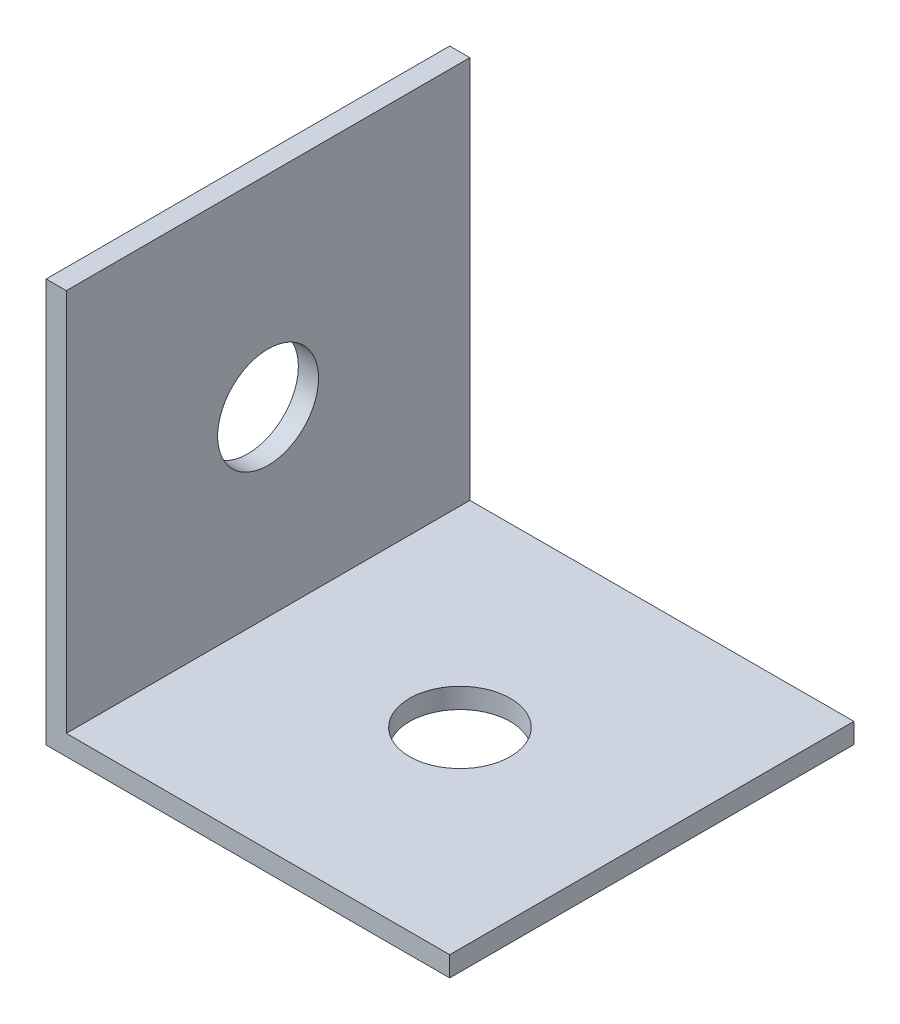
SolidWorks part; units mm, degrees
ref_plane "Front Plane" through (0, 0, 0) normal (0, 0, 1) x (1, 0, 0)
ref_plane "Top Plane" through (0, 0, 0) normal (0, 1, 0) x (1, 0, 0)
ref_plane "Right Plane" through (0, 0, 0) normal (1, 0, 0) x (0, 0, -1)
sketch "Sketch1" plane through (0, 0, 0) normal (1, 0, 0) x (0, 0, -1)
  line L1 (-12.7, 12.7) -> (12.7, 12.7)
  line L2 (-12.7, 12.7) -> (-12.7, -12.7)
  line L3 (-12.7, -12.7) -> (12.7, -12.7)
  line L4 (12.7, 12.7) -> (12.7, -12.7)
  line L5 (-12.7, 12.7) -> (12.7, -12.7) construction
  line L6 (-12.7, -12.7) -> (12.7, 12.7) construction
  point P0 (0, 0)
  dimension "D1" = 25.4
  dimension "D2" = 25.4
extrude "Boss-Extrude1" add sketch "Sketch1" along normal blind 1.27
sketch "Sketch2" plane through (0, -12.7, 0) normal (0, -1, 0) x (1, 0, 0)
  line L0 (1.27, 12.7) -> (25.4, 12.7)
  line L1 (25.4, 12.7) -> (25.4, -12.7387)
  line L2 (25.4, -12.7387) -> (1.27, -12.7)
  line L3 (1.27, 12.7) -> (1.27, -12.7)
  dimension "D1" = 24.13
extrude "Boss-Extrude2" add sketch "Sketch2" against normal blind 1.27
sketch "Sketch3" plane through (1.27, 0, 0) normal (1, 0, 0) x (0, 0, -1)
  circle A0 centre (0, 0) radius 3.175
extrude "Cut-Extrude1" cut sketch "Sketch3" against normal blind 1.27
sketch "Sketch4" plane through (0, -11.43, 0) normal (0, 1, 0) x (1, 0, 0)
  line L0 (13.335, 12.7193) -> (13.335, -12.7) construction
  line L1 (1.27, 12.7) -> (25.4, 12.7387) construction
  line L2 (25.4, -12.7) -> (1.27, -12.7) construction
  circle A0 centre (13.335, 0.0097) radius 3.175
extrude "Cut-Extrude2" cut sketch "Sketch4" against normal blind 1.27
